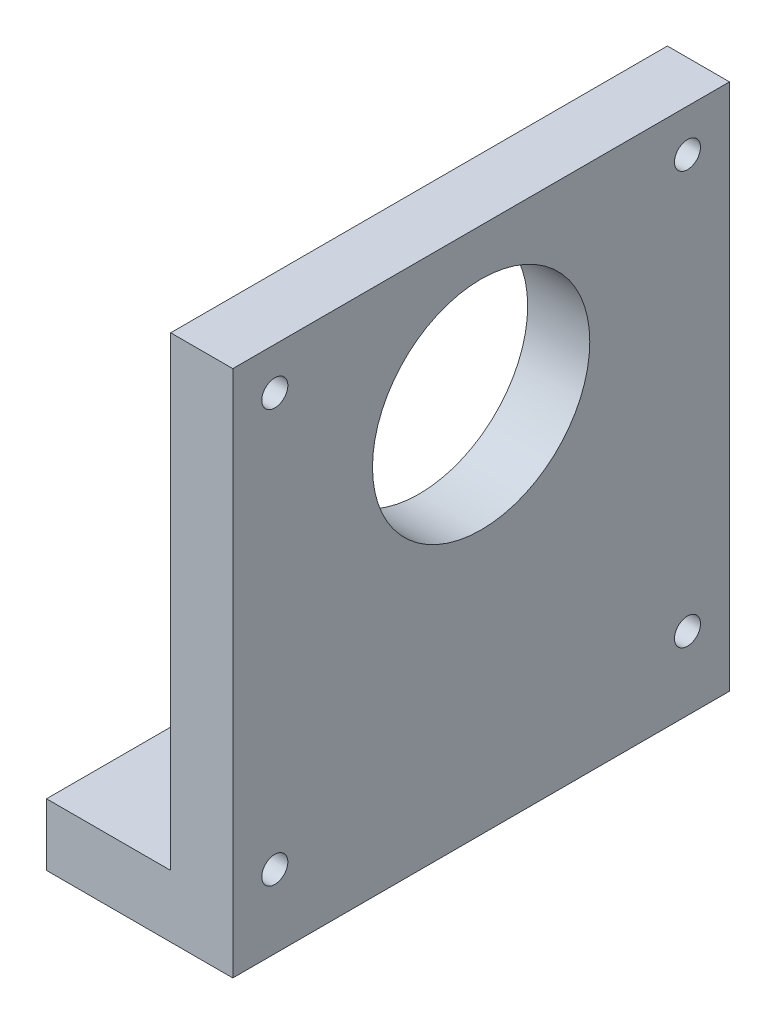
SolidWorks part; units mm, degrees
ref_plane "前视基准面" through (0, 0, 0) normal (0, 0, 1) x (1, 0, 0)
ref_plane "上视基准面" through (0, 0, 0) normal (0, 1, 0) x (1, 0, 0)
ref_plane "右视基准面" through (0, 0, 0) normal (1, 0, 0) x (0, 0, -1)
sketch "草图1" plane through (0, 0, 0) normal (0, 0, 1) x (1, 0, 0)
  line L0 (-20, 0) -> (10, 0)
  line L2 (0, 10) -> (0, 85)
  line L3 (0, 85) -> (10, 85)
  line L4 (10, 0) -> (10, 85)
  line L7 (0, 10) -> (-20, 10)
  line L8 (-20, 0) -> (-20, 10)
  dimension "D1" = 10
  dimension "D2" = 85
  dimension "D3" = 30
  dimension "D4" = 10
extrude "拉伸1" add sketch "草图1" along normal mid plane 80
sketch "草图2" plane through (0, 10, 0) normal (0, 1, 0) x (1, 0, 0)
  line L0 (-13.5, 25) -> (-13.5, 15)
  line L1 (-6.5, 25) -> (-6.5, 15)
  line L2 (-20, -40) -> (-20, 40) construction
  line L3 (-13.5, -15) -> (-13.5, -25)
  line L4 (-6.5, -15) -> (-6.5, -25)
  arc A0 (-6.5, 25) -> (-13.5, 25) centre (-10, 25) ccw
  arc A1 (-13.5, 15) -> (-6.5, 15) centre (-10, 15) ccw
  arc A2 (-6.5, -15) -> (-13.5, -15) centre (-10, -15) ccw
  arc A3 (-13.5, -25) -> (-6.5, -25) centre (-10, -25) ccw
  dimension "D1" = 7
  dimension "D2" = 7
  dimension "D3" = 10
  dimension "D5" = 15
  dimension "D4" = 10
extrude "拉伸2" cut sketch "草图2" against normal up to next
hole_wizard "M5 螺纹孔1" positions "草图4" profile "草图3" tap size "M5" standard "GB"
sketch "草图4" plane through (0, 0, 0) normal (-1, 0, 0) x (0, 0, 1)
  circle A0 centre (33.234, 78.234) radius 3 construction
  circle A1 centre (33.234, 78.234) radius 3
  circle A2 centre (-33.234, 78.234) radius 3 construction
  circle A3 centre (-33.234, 78.234) radius 3
  circle A4 centre (33.234, 11.766) radius 3 construction
  circle A5 centre (33.234, 11.766) radius 3
  circle A6 centre (-33.234, 11.766) radius 3 construction
  circle A7 centre (-33.234, 11.766) radius 3
  point P0 (33.234, 78.234)
  point P1 (-33.234, 78.234)
  point P3 (-33.234, 11.766)
  point P5 (33.234, 11.766)
sketch "草图3" plane through (0, 78.234, 33.234) normal (0, 1, 0) x (0, 0, 1)
  line L0 (0, 0) -> (0, 15.2618)
  line L1 (0, 15.2618) -> (2.1, 14)
  line L2 (2.1, 14) -> (2.1, 0)
  line L5 (2.1, 0) -> (0, 0)
  line L10 (0, 15.2618) -> (-2.1, 14) construction
  line L11 (0, -6.35) -> (0, 107.95) construction
  dimension "螺纹孔钻头直径" = 4.2
  dimension "螺纹孔钻头深度" = 14
  dimension "导头角度" = 118
cosmetic thread "孔螺蚊线1" parameters "D1"=10, "D2"=5
cosmetic thread "孔螺蚊线2" parameters "D1"=10, "D2"=5
cosmetic thread "孔螺蚊线3" parameters "D1"=10, "D2"=5
cosmetic thread "孔螺蚊线4" parameters "D1"=10, "D2"=5
sketch "草图5" plane through (0, 0, 0) normal (-1, 0, 0) x (0, 0, 1)
  circle A0 centre (0, 60) radius 17.5
  arc A1 (-2, 64.5826) -> (2, 64.5826) centre (0, 60) ccw construction
  arc A2 (-2, 64.5826) -> (2, 64.5826) centre (0, 60) ccw construction
  dimension "D1" = 35
extrude "拉伸3" cut sketch "草图5" against normal blind 10
